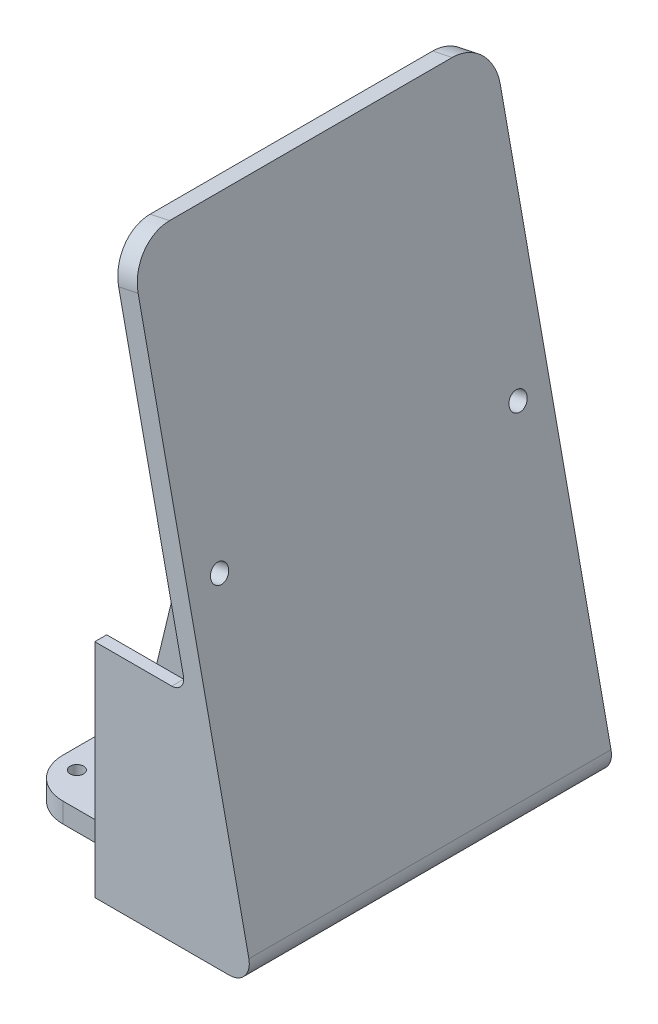
SolidWorks part; units mm, degrees
material "ABS"
ref_plane "前视基准面" through (0, 0, 0) normal (0, 0, 1) x (1, 0, 0)
ref_plane "上视基准面" through (0, 0, 0) normal (0, 1, 0) x (1, 0, 0)
ref_plane "右视基准面" through (0, 0, 0) normal (1, 0, 0) x (0, 0, -1)
sketch "草图2" plane through (0, 0, 0) normal (0, 0, 1) x (1, 0, 0)
  line L0 (0, 0) -> (-31.1868, 146.7221)
  line L1 (-31.1868, 146.7221) -> (-36.0775, 145.6826)
  line L2 (-36.0775, 145.6826) -> (-6.1745, 5)
  line L3 (-6.1745, 5) -> (-70, 5)
  line L4 (-70, 5) -> (-70, 0)
  line L5 (-70, 0) -> (0, 0)
  line L6 (-36.0775, 145.6826) -> (-101.0775, 145.6826) construction
  line L8 (-31.1868, 146.7221) -> (-18.2752, 149.4666) construction
  line L9 (-18.2752, 149.4666) -> (12.9115, 2.7444) construction
  line L10 (12.9115, 2.7444) -> (0, 0) construction
  dimension "D1" = 150
  dimension "D2" = 5
  dimension "D3" = 5
  dimension "D4" = 70
  dimension "D5" = 78
  dimension "D6" = 65
  dimension "D7" = 13.2
extrude "凸台-拉伸1" add sketch "草图2" along normal blind 85
sketch "草图3" plane through (0, 0, 0) normal (0.9781, 0.2079, 0) x (0, 0, -1)
  line L0 (-42.5, 150) -> (-42.5, 0) construction
  line L1 (-85, 150) -> (0, 150) construction
  line L2 (-85, 0) -> (0, 0) construction
  line L4 (-80, 5) -> (-5, 5) construction
  line L5 (-80, 5) -> (-80, 80) construction
  line L6 (-80, 80) -> (-5, 80) construction
  line L7 (-5, 5) -> (-5, 80) construction
  line L8 (-80, 5) -> (-5, 80) construction
  line L9 (-80, 80) -> (-5, 5) construction
  circle A0 centre (-80, 80) radius 2.25
  circle A1 centre (-5, 80) radius 2.25
  circle A2 centre (-5, 5) radius 2.25 construction
  circle A3 centre (-80, 5) radius 2.25 construction
  point P6 (-42.5, 42.5)
  dimension "D4" = 4.5
  dimension "D1" = 75
  dimension "D2" = 75
  dimension "D3" = 70
extrude "切除-拉伸1" cut sketch "草图3" against normal blind 20
sketch "草图4" plane through (0, 0, 85) normal (0, 0, 1) x (1, 0, 0)
  line L0 (-36.0775, 145.6826) -> (-70, 5) construction
  line L1 (-70, 5) -> (-6.1745, 5) construction
  line L2 (-6.1745, 5) -> (-36.0775, 145.6826) construction
  line L3 (-36.0775, 145.6826) -> (-70, 5)
  line L4 (-70, 5) -> (-70, 0)
  line L5 (-70, 0) -> (0, 0)
  line L6 (0, 0) -> (-31.1868, 146.7221)
  line L7 (-31.1868, 146.7221) -> (-36.0775, 145.6826)
extrude "凸台-拉伸2" add sketch "草图4" along normal blind 3
sketch "草图5" plane through (0, 0, 0) normal (0, 0, -1) x (-1, 0, 0)
  line L0 (36.0775, 145.6826) -> (6.1745, 5) construction
  line L1 (6.1745, 5) -> (70, 5) construction
  line L2 (70, 5) -> (36.0775, 145.6826) construction
  line L3 (36.0775, 145.6826) -> (31.1868, 146.7221)
  line L4 (31.1868, 146.7221) -> (0, 0)
  line L5 (0, 0) -> (70, 0)
  line L6 (70, 0) -> (70, 5)
  line L7 (70, 5) -> (36.0775, 145.6826)
extrude "凸台-拉伸3" add sketch "草图5" along normal blind 3
fillet "圆角1" radius 5 1 edges at (0, 0, 42.5)
sketch "草图6" plane through (0, 0, 0) normal (0, -1, 0) x (1, 0, 0)
  line L0 (-70, 42.5) -> (-6.1745, 42.5) construction
  line L1 (-70, 88) -> (-70, -3) construction
  line L2 (-6.1745, -3) -> (-6.1745, 88) construction
  line L3 (-70, 88) -> (-70, -3) construction
  line L8 (-65, 67.5) -> (-35, 67.5) construction
  line L10 (-65, 67.5) -> (-65, 17.5) construction
  line L11 (-65, 17.5) -> (-35, 17.5) construction
  line L12 (-35, 67.5) -> (-35, 17.5) construction
  line L13 (-65, 67.5) -> (-35, 17.5) construction
  line L14 (-65, 17.5) -> (-35, 67.5) construction
  circle A0 centre (-65, 67.5) radius 1.7
  circle A1 centre (-35, 67.5) radius 1.7
  circle A4 centre (-65, 17.5) radius 1.7
  circle A5 centre (-35, 17.5) radius 1.7
  point P6 (-50, 42.5)
  dimension "D3" = 20
  dimension "D4" = 3.4
  dimension "D1" = 30
  dimension "D2" = 50
extrude "切除-拉伸2" cut sketch "草图6" against normal blind 10
sketch "草图7" plane through (0, 0, 0) normal (0, 0, 1) x (1, 0, 0)
  line L0 (-36.0775, 145.6826) -> (-16.9474, 55.6826)
  line L1 (-36.0775, 145.6826) -> (-6.1745, 5) construction
  line L2 (-16.9474, 55.6826) -> (-57.779, 55.6826)
  line L4 (-57.779, 55.6826) -> (-36.0775, 145.6826)
  line L5 (-36.0775, 145.6826) -> (-70, 5) construction
  dimension "D1" = 90
extrude "切除-拉伸3" cut sketch "草图7" against normal through all both and the other way through all
fillet "圆角2" [suppressed] radius 4
sketch "草图8" plane through (0, 0, 0) normal (0, -1, 0) x (1, 0, 0)
  line L1 (-70, 88) -> (-40, 88)
  line L2 (-70, 88) -> (-70, 76)
  line L3 (-70, 76) -> (-40, 76)
  line L4 (-40, 88) -> (-40, 76)
  line L5 (-70, -3) -> (-40, -3)
  line L6 (-70, -3) -> (-70, 9)
  line L7 (-70, 9) -> (-40, 9)
  line L8 (-40, -3) -> (-40, 9)
  dimension "D1" = 12
  dimension "D2" = 12
  dimension "D3" = 30
  dimension "D4" = 30
extrude "切除-拉伸4" cut sketch "草图8" against normal blind 150
fillet "圆角3" [suppressed] radius 4
ref_plane "基准面1" through (0, 0, 45) normal (0, 0, 1) x (1, 0, 0)
sketch "草图9" plane through (0, 0, 45) normal (0, 0, 1) x (1, 0, 0)
  line L0 (-36.0775, 145.6826) -> (-70, 5)
  line L1 (-36.0775, 145.6826) -> (-6.1745, 5) construction
  line L2 (-6.1745, 5) -> (-70, 5) construction
  line L3 (-70, 5) -> (-6.1745, 5)
  line L4 (-6.1745, 5) -> (-36.0775, 145.6826)
  point P6 (-36.0775, 145.6826)
  point P10 (-70, 5)
extrude "凸台-拉伸4" add sketch "草图9" against normal blind 5
fillet "圆角4" radius 3 12 edges at (-16.9474, 55.6826, -1.5) (-6.1745, 5, 65) (-6.1745, 5, 20) (-21.126, 75.3413, 40) (-38.0872, 5, 40) (-21.126, 75.3413, 45) (-38.0872, 5, 45) (-23.0872, 5, 85) (-23.0872, 5, 0) (-11.5609, 30.3413, 0) (-11.5609, 30.3413, 85) (-16.9474, 55.6826, 86.5)
fillet "圆角5" radius 10 4 edges at (-70, 2.5, 9) (-70, 2.5, 76) (-40, 2.5, 76) (-40, 2.5, 9)
fillet "圆角6" radius 10 2 edges at (-33.6321, 146.2024, -3) (-33.6321, 146.2024, 88)
